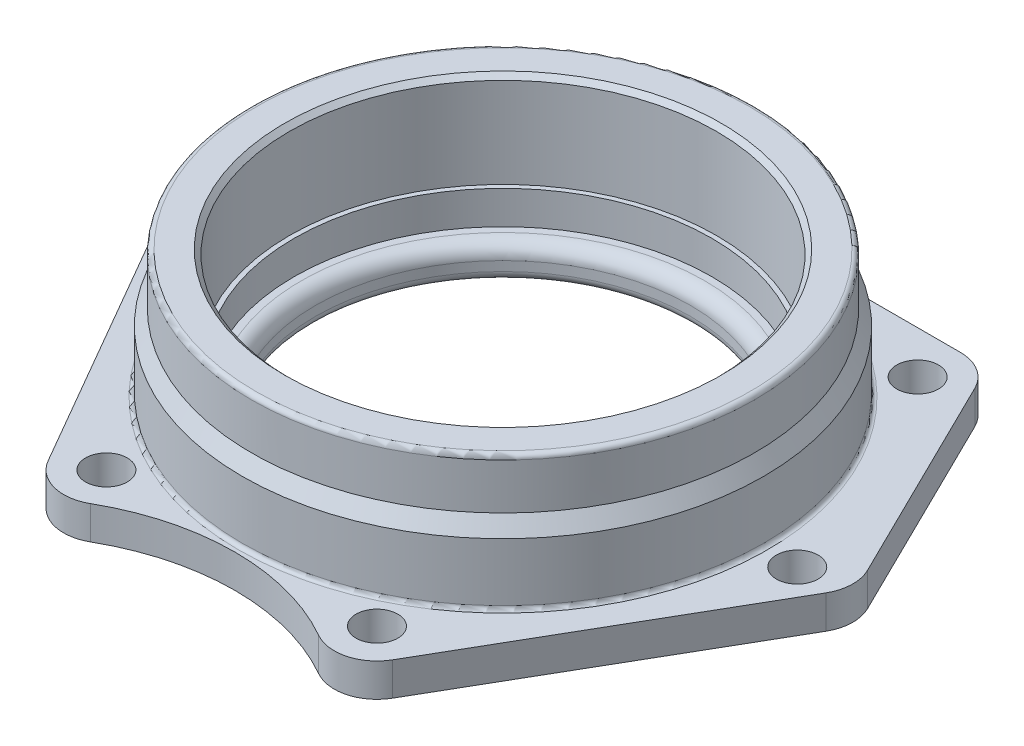
SolidWorks part; units mm, degrees
material "0.6025 (EN-GJL-250)"
ref_plane "Front Plane" through (0, 0, 0) normal (0, 0, 1) x (1, 0, 0)
ref_plane "Top Plane" through (0, 0, 0) normal (0, 1, 0) x (1, 0, 0)
ref_plane "Right Plane" through (0, 0, 0) normal (1, 0, 0) x (0, 0, -1)
sketch "Sketch1" plane through (0, 0, 0) normal (0, 1, 0) x (1, 0, 0)
  line L0 (0, 0) -> (0, 62) construction
  line L1 (0, 0) -> (62, 0) construction
  line L2 (0, 0) -> (-40.0018, 47.3693) construction
  line L3 (0, 0) -> (-61.9367, 2.8017) construction
  line L4 (0, 0) -> (-28.5036, -55.0595) construction
  line L5 (0, 0) -> (28.5036, -55.0595) construction
  line L6 (0, 0) -> (61.9367, 2.8017) construction
  line L7 (0, 0) -> (40.0018, 47.3693) construction
  line L8 (-40.0018, 56.3693) -> (40.0018, 56.3693)
  line L10 (48.0768, 51.3436) -> (70.0116, 6.776)
  line L11 (69.7293, -1.701) -> (36.2962, -59.5622)
  line L12 (-69.7293, -1.701) -> (-36.2962, -59.5622)
  line L13 (-48.0768, 51.3436) -> (-70.0116, 6.776)
  circle A0 centre (0, 0) radius 62 construction
  arc A2 (-70.0116, 6.776) -> (-69.7293, -1.701) centre (-61.9367, 2.8017) ccw
  arc A5 (70.0116, 6.776) -> (69.7293, -1.701) centre (61.9367, 2.8017) cw
  arc A6 (40.0018, 56.3693) -> (48.0768, 51.3436) centre (40.0018, 47.3693) cw
  arc A7 (-40.0018, 56.3693) -> (-48.0768, 51.3436) centre (-40.0018, 47.3693) ccw
  arc A8 (53.3839, 0) -> (52.9459, 2.395) centre (61.9367, 2.8017) cw
  arc A9 (-36.2962, -59.5622) -> (-24.0421, -62.8759) centre (-28.5036, -55.0595) ccw
  arc A10 (24.0421, -62.8759) -> (36.2962, -59.5622) centre (28.5036, -55.0595) ccw
  arc A11 (24.0421, -62.8759) -> (-24.0421, -62.8759) centre (0, -104.9974) ccw
  dimension "D1" = 124
  dimension "D5" = 18
  dimension "D6" = 48.5
  dimension "D2" = 40.18
  dimension "D3" = 47.23
  dimension "D4" = 65.22
extrude "Boss-Extrude1" add sketch "Sketch1" along normal blind 7
sketch "Sketch4" plane through (0, 0, 0) normal (1, 0, 0) x (0, 0, -1)
  line L0 (0, 0) -> (0, 34)
  line L1 (0, 34) -> (53, 34)
  line L2 (53, 34) -> (53, 23.3336)
  line L3 (53, 23.3336) -> (54.9247, 20)
  line L4 (54.9247, 20) -> (54.9247, 0)
  line L5 (51.3436, 0) -> (6.776, 0) construction
  line L6 (54.9247, 0) -> (0, 0)
  line L7 (56.3693, 7) -> (51.3436, 7) construction
  line L8 (51.3436, 7) -> (6.776, 7) construction
  dimension "D1" = 53
  dimension "D2" = 54.9247
  dimension "D3" = 30
  dimension "D4" = 13
  dimension "D5" = 27
revolve "Revolve2" add sketch "Sketch4" angle 360 about L0
sketch "Sketch5" plane through (0, 34, 0) normal (0, 1, 0) x (1, 0, 0)
  circle A0 centre (0, 0) radius 45
  dimension "D1" = 90
extrude "Cut-Extrude1" cut sketch "Sketch5" against normal blind 20
sketch "Sketch6" plane through (0, 14, 0) normal (0, 1, 0) x (1, 0, 0)
  circle A0 centre (0, 0) radius 44
  dimension "D1" = 88
extrude "Cut-Extrude3" cut sketch "Sketch6" against normal blind 7
sketch "Sketch8" plane through (0, 7, 0) normal (0, 1, 0) x (1, 0, 0)
  circle A0 centre (0, 0) radius 39.5
  dimension "D1" = 79
extrude "Cut-Extrude4" cut sketch "Sketch8" against normal blind 7
hole_wizard "Ø8.8 (8.8) Diameter Hole1" positions "Sketch12" profile "Sketch13" hole size "Ø8.8" standard "ISO" end condition through all
sketch "Sketch12" plane through (0, 7, 0) normal (0, 1, 0) x (1, 0, 0)
  circle A0 centre (0, 0) radius 62 construction
  point P0 (-62, 0)
  point P4 (62, 0)
  point P7 (28.5036, -55.0595)
  point P10 (-28.5036, -55.0595)
  point P13 (-40.0018, 47.3693)
  point P16 (40.0018, 47.3693)
sketch "Sketch13" plane through (-62, 7, 0) normal (1, 0, 0) x (0, 0, 1)
  line L0 (0, 0) -> (0, 7)
  line L1 (0, 7) -> (4.4, 7)
  line L2 (4.4, 7) -> (4.4, 0)
  line L5 (4.4, 0) -> (0, 0)
  line L11 (0, -6.35) -> (0, 107.95) construction
  dimension "Thru Hole Dia." = 8.8
  dimension "Thru Hole Depth" = 7
chamfer "Chamfer1" distance 1 angle 45 1 edges at (0, 34, 45)
fillet "Fillet1" radius 1 1 edges at (0, 34, -53)
fillet "Fillet3" radius 2 1 edges at (0, 0, 39.5)
fillet "Fillet4" radius 0.8 1 edges at (0, 7, 54.9247)
fillet "Fillet5" radius 3 1 edges at (0, 7, 39.5)
sketch "Sketch14" plane through (0, 0, 0) normal (0, -1, 0) x (1, 0, 0)
  line L0 (-54.9744, -11.5442) -> (-45.5452, -34.8505) construction
  text T0 "ADITYA"
extrude "Boss-Extrude2" add sketch "Sketch14" along normal blind 1
